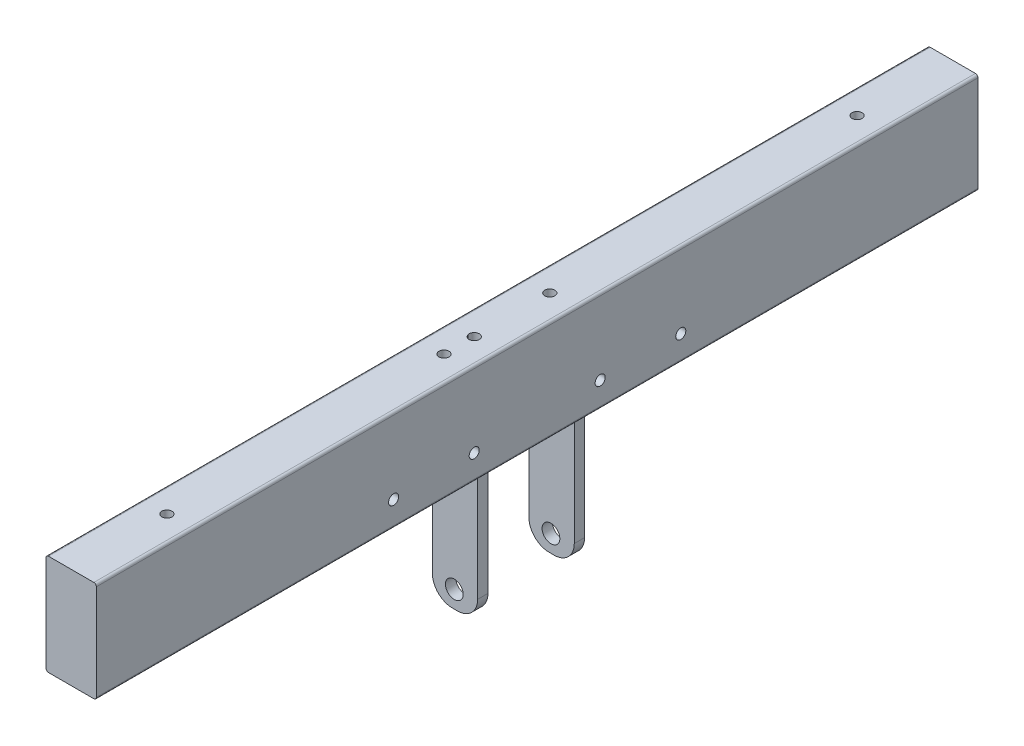
SolidWorks part; units mm, degrees
ref_plane "前视基准面" through (0, 0, 0) normal (0, 0, 1) x (1, 0, 0)
ref_plane "上视基准面" through (0, 0, 0) normal (0, 1, 0) x (1, 0, 0)
ref_plane "右视基准面" through (0, 0, 0) normal (1, 0, 0) x (0, 0, -1)
sketch "草图1" plane through (0, 0, 0) normal (0, 0, 1) x (1, 0, 0)
  line L1 (0, 0) -> (20, 0)
  line L2 (0, 0) -> (0, 40)
  line L3 (0, 40) -> (20, 40)
  line L4 (20, 0) -> (20, 40)
  dimension "D1" = 20
  dimension "D2" = 40
extrude "凸台-拉伸1" add sketch "草图1" along normal blind 350
fillet "圆角1" radius 1 4 edges at (0, 0, 175) (20, 0, 175) (20, 40, 175) (0, 40, 175)
sketch "草图2" plane through (0, 0, 0) normal (-1, 0, 0) x (0, 0, 1)
  line L0 (0, 39) -> (0, 1) construction
  line L1 (350, 0) -> (0, 0) construction
  line L2 (350, 39) -> (350, 1) construction
  circle A0 centre (118, 10) radius 2
  circle A1 centre (232, 10) radius 2
  circle A2 centre (150, 10) radius 2
  circle A3 centre (200, 10) radius 2
  dimension "D3" = 4
  dimension "D1" = 118
  dimension "D2" = 10
  dimension "D4" = 118
  dimension "D5" = 32
  dimension "D6" = 32
extrude "切除-拉伸1" cut sketch "草图2" against normal blind 310
sketch "草图3" plane through (0, 40, 0) normal (0, 1, 0) x (1, 0, 0)
  line L0 (19, 0) -> (1, 0) construction
  line L1 (20, 0) -> (20, -350) construction
  line L2 (19, -350) -> (1, -350) construction
  line L3 (19, -350) -> (19, 0) construction
  circle A0 centre (10, -38) radius 2
  circle A1 centre (10, -312) radius 2
  circle A2 centre (10, -160) radius 2
  circle A3 centre (10, -190) radius 2
  circle A4 centre (10, -202) radius 2
  point P16 (19, -175)
  dimension "D3" = 4
  dimension "D1" = 38
  dimension "D2" = 10
  dimension "D4" = 38
  dimension "D5" = 30
  dimension "D6" = 15
  dimension "D7" = 12
extrude "切除-拉伸2" cut sketch "草图3" against normal blind 90
sketch "草图4" plane through (0, 0, 0) normal (0, -1, 0) x (1, 0, 0)
  line L0 (1, 350) -> (1, 0) construction
  line L1 (1, 197.6417) -> (19, 197.6417)
  line L2 (1, 197.6417) -> (1, 193.5314)
  line L3 (1, 193.5314) -> (19, 193.5314)
  line L4 (19, 197.6417) -> (19, 193.5314)
  line L5 (19, 0) -> (19, 350) construction
  line L7 (1, 159.2788) -> (19, 159.2788)
  line L8 (1, 159.2788) -> (1, 155.1685)
  line L9 (1, 155.1685) -> (19, 155.1685)
  line L10 (19, 159.2788) -> (19, 155.1685)
extrude "凸台-拉伸2" add sketch "草图4" along normal blind 50
sketch "草图5" plane through (0, 0, 155.1685) normal (0, 0, -1) x (-1, 0, 0)
  circle A0 centre (-9.7439, -43.1703) radius 3.5253
extrude "切除-拉伸3" cut sketch "草图5" against normal blind 50
fillet "圆角2" radius 8 4 edges at (1, -50, 157.2236) (1, -50, 195.5866) (19, -50, 195.5866) (19, -50, 157.2236)
